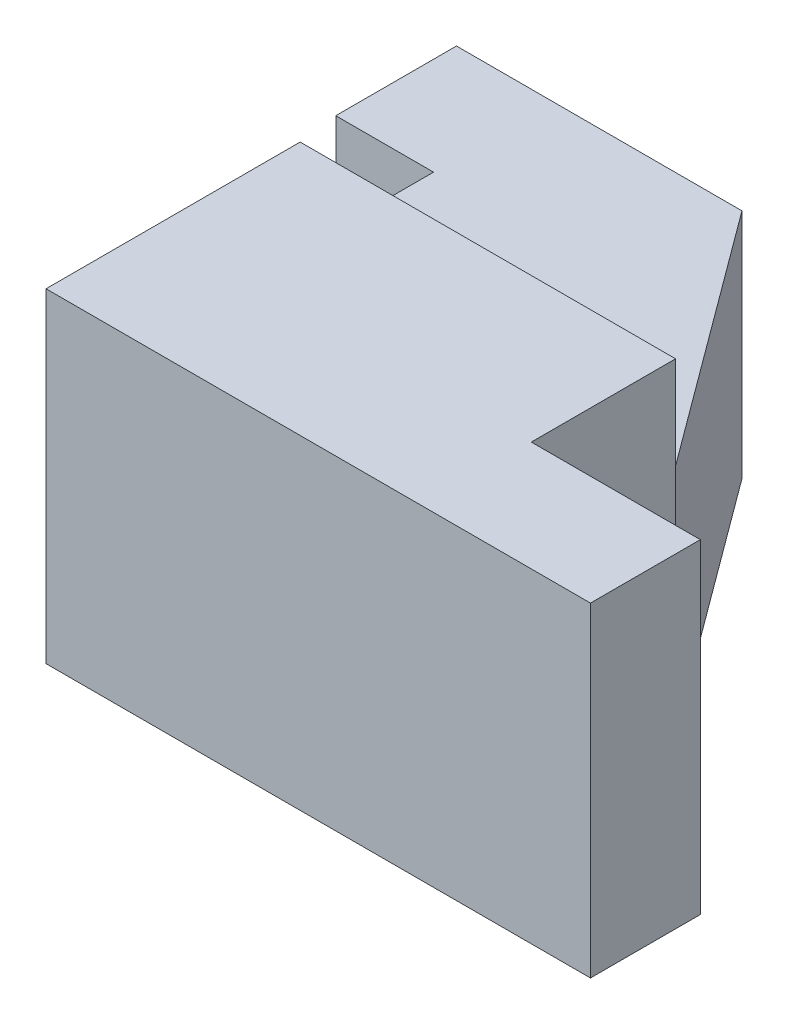
SolidWorks part; units mm, degrees
ref_plane "Front Plane" through (0, 0, 0) normal (0, 0, 1) x (1, 0, 0)
ref_plane "Top Plane" through (0, 0, 0) normal (0, 1, 0) x (1, 0, 0)
ref_plane "Right Plane" through (0, 0, 0) normal (1, 0, 0) x (0, 0, -1)
sketch "Sketch1" plane through (0, 0, 0) normal (0, 1, 0) x (1, 0, 0)
  line L0 (20.2342, 54.7819) -> (40.4683, 27.3909)
  line L1 (0, 0) -> (40.4683, 0)
  line L2 (0, 0) -> (0, 41.7696)
  line L3 (0, 54.7819) -> (20.2342, 54.7819)
  line L4 (40.4683, 11.8412) -> (40.4683, 27.3909)
  line L5 (0, 54.7819) -> (-10.54, 54.7819)
  line L7 (0, 41.7696) -> (-10.54, 41.7696)
  line L8 (-10.54, 54.7819) -> (-10.54, 41.7696)
  line L9 (40.4683, 0) -> (58.6856, 0)
  line L11 (40.4683, 11.8412) -> (58.6856, 11.8412)
  line L12 (58.6856, 0) -> (58.6856, 11.8412)
extrude "Boss-Extrude1" add sketch "Sketch1" along normal blind 35 contours L4 L0 L3 L5 L8 L7 L2 L1 L9 L12 L11
sketch "Sketch2" plane through (0, 35, 0) normal (0, 1, 0) x (1, 0, 0)
  line L0 (40.4683, 27.3909) -> (0, 27.3909)
  line L9 (58.6856, 11.8412) -> (40.4683, 11.8412)
  line L10 (40.4683, 11.8412) -> (40.4683, 27.3909)
  line L11 (40.4683, 27.3909) -> (20.2342, 54.7819)
  line L12 (20.2342, 54.7819) -> (-10.54, 54.7819)
  line L13 (-10.54, 54.7819) -> (-10.54, 41.7696)
  line L14 (-10.54, 41.7696) -> (0, 41.7696)
  line L15 (0, 41.7696) -> (0, 0)
  line L16 (0, 0) -> (58.6856, 0)
  line L17 (58.6856, 0) -> (58.6856, 11.8412)
  line L20 (40.4683, 27.3909) -> (20.2342, 54.7819)
  line L21 (20.2342, 54.7819) -> (-10.54, 54.7819)
  line L22 (-10.54, 54.7819) -> (-10.54, 41.7696)
  line L23 (-10.54, 41.7696) -> (0, 41.7696)
  line L24 (0, 41.7696) -> (0, 0)
  line M12 (40.4683, 27.3909) -> (20.2342, 54.7819)
  line M13 (20.2342, 54.7819) -> (-10.54, 54.7819)
  line M14 (-10.54, 54.7819) -> (-10.54, 41.7696)
  line M15 (-10.54, 41.7696) -> (0, 41.7696)
  line M16 (0, 41.7696) -> (0, 0)
  dimension "D1" = 0
extrude "Cut-Extrude1" cut sketch "Sketch2" against normal blind 10 contours L0 M12 M13 M14 M15 M16
sketch "Sketch3" plane through (40.4683, 0, 0) normal (1, 0, 0) x (0, 0, -1)
  line L0 (15.608, 35) -> (15.608, 0) construction
  line L1 (11.8412, 35) -> (27.3909, 35) construction
  line L2 (11.8412, 0) -> (27.3909, 0) construction
  text T0 "FRONT" font "Austere Black SSi" height 3.5
extrude "Boss-Extrude2" add sketch "Sketch3" along normal blind 1
